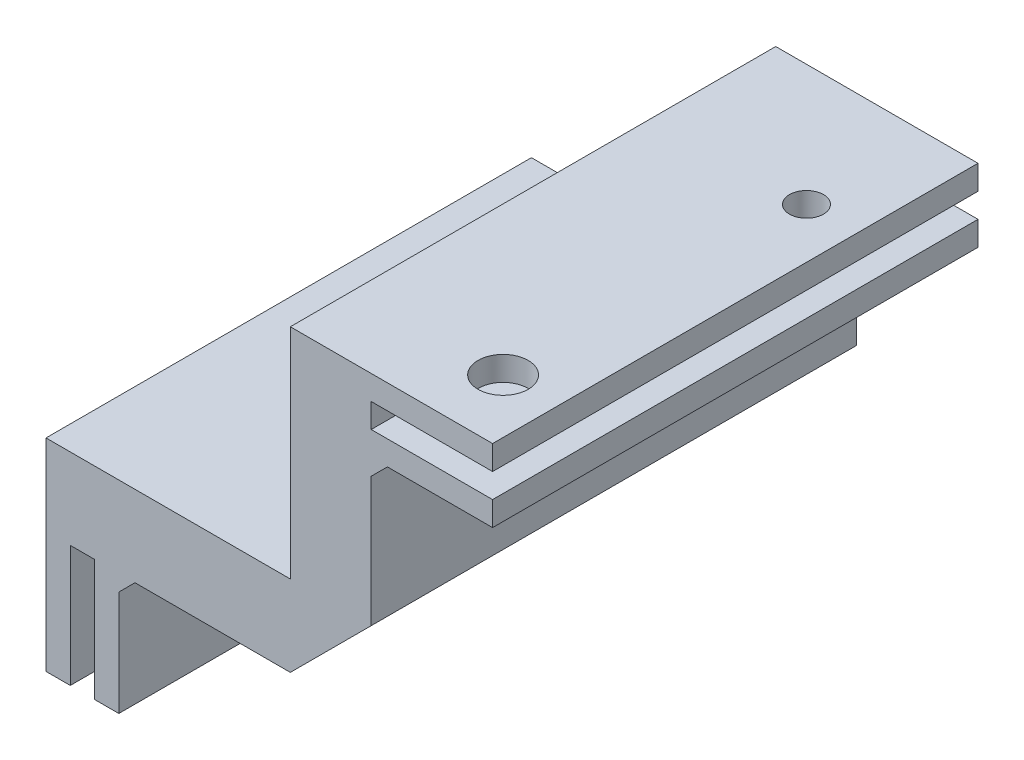
SolidWorks part; units mm, degrees
material "ABS"
ref_plane "Płaszczyzna przednia" through (0, 0, 0) normal (0, 0, 1) x (1, 0, 0)
ref_plane "Płaszczyzna górna" through (0, 0, 0) normal (0, 1, 0) x (1, 0, 0)
ref_plane "Płaszczyzna prawa" through (0, 0, 0) normal (1, 0, 0) x (0, 0, -1)
sketch "Szkic1" plane through (0, 0, 0) normal (0, 0, 1) x (1, 0, 0)
  line L0 (0, 0) -> (3, 0)
  line L1 (3, 0) -> (3, 15)
  line L2 (3, 15) -> (6, 15)
  line L3 (6, 15) -> (6, 0)
  line L4 (6, 0) -> (9, 0)
  line L5 (9, 0) -> (9, 15)
  line L6 (0, 0) -> (0, 25)
  line L7 (0, 25) -> (9, 25)
  line L8 (9, 25) -> (30.2, 25)
  line L9 (9, 15) -> (40.2, 15)
  line L10 (30.2, 52) -> (40.2, 52)
  line L11 (30.2, 25) -> (30.2, 52)
  line L12 (40.2, 52) -> (55.2, 52)
  line L13 (55.2, 52) -> (55.2, 49)
  line L14 (55.2, 49) -> (40.2, 49)
  line L15 (40.2, 49) -> (40.2, 46)
  line L16 (40.2, 46) -> (55.2, 46)
  line L17 (55.2, 46) -> (55.2, 43)
  line L18 (55.2, 43) -> (40.2, 43)
  line L19 (40.2, 43) -> (40.2, 15)
  point P23 (40.2, 47.5)
  dimension "D1" = 3
  dimension "D2" = 3
  dimension "D3" = 3
  dimension "D4" = 15
  dimension "D5" = 10
  dimension "D6" = 21.2
  dimension "D7" = 37
  dimension "D8" = 10
  dimension "D9" = 15
  dimension "D10" = 10
  dimension "D11" = 3
  dimension "D12" = 3
  dimension "D13" = 3
extrude "Dodanie-wyciągnięcie1" add sketch "Szkic1" along normal blind 60
chamfer "Sfazowanie1" distance 10 angle 45 1 edges at (40.2, 15, 30)
chamfer "Sfazowanie2" distance 2 angle 45 2 edges at (40.2, 43, 30) (9, 15, 30)
sketch "Szkic4" plane through (0, 43, 0) normal (0, -1, 0) x (1, 0, 0)
  line L0 (42.2, 60) -> (55.2, 60) construction
  line L1 (40.2, 0) -> (40.2, 60) construction
  circle A0 centre (48.5, 52) radius 3.1
  dimension "D1" = 6.2
  dimension "D2" = 8
  dimension "D3" = 8.3
extrude "Wytnij-wyciągnięcie1" cut sketch "Szkic4" against normal blind 10
sketch "Szkic5" plane through (0, 43, 0) normal (0, -1, 0) x (1, 0, 0)
  line L1 (40.2, 0) -> (40.2, 60) construction
  line L2 (42.2, 0) -> (55.2, 0) construction
  circle A0 centre (49, 15) radius 2.1
  dimension "D1" = 4.2
  dimension "D2" = 8.8
  dimension "D3" = 15
extrude "Wytnij-wyciągnięcie2" cut sketch "Szkic5" against normal blind 10
sketch "Szkic6" plane through (9, 0, 0) normal (1, 0, 0) x (0, 0, -1)
  line L0 (0, 0) -> (0, 13) construction
  line L1 (0, 15) -> (-60, 15) construction
  circle A0 centre (-15, 6) radius 2.1
  dimension "D1" = 4.2
  dimension "D3" = 9
  dimension "D2" = 15
extrude "Wytnij-wyciągnięcie3" cut sketch "Szkic6" against normal blind 10
